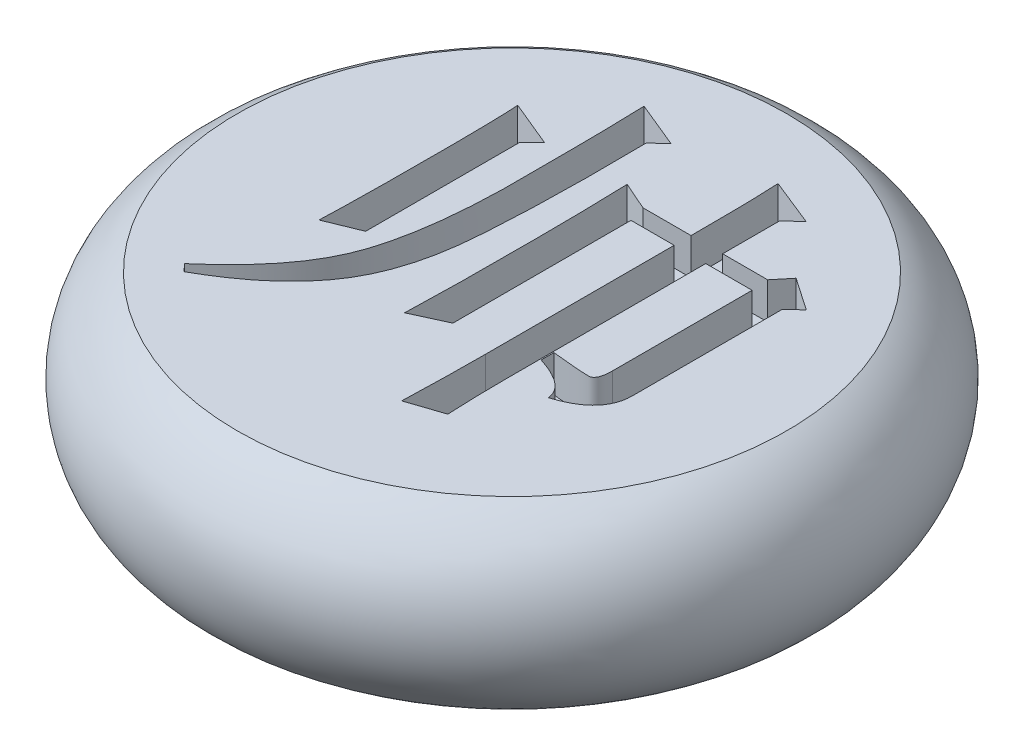
SolidWorks part; units mm, degrees
ref_plane "前视基准面" through (0, 0, 0) normal (0, 0, 1) x (1, 0, 0)
ref_plane "上视基准面" through (0, 0, 0) normal (0, 1, 0) x (1, 0, 0)
ref_plane "右视基准面" through (0, 0, 0) normal (1, 0, 0) x (0, 0, -1)
sketch "草图1" plane through (0, 0, 0) normal (0, 0, 1) x (1, 0, 0)
  line L0 (0, 13.4115) -> (0, -13.4115) construction
  line L1 (0, 0) -> (15, 0)
  line L4 (0, 0) -> (0, 10)
  line L5 (0, 10) -> (15, 10)
  line L6 (-18, 5) -> (18, 5) construction
  arc A1 (15, 0) -> (15, 10) centre (12.3333, 5) ccw
  point P2 (0, 0)
  point P4 (0, 0)
  point P10 (0, 5)
  point P14 (0, 0)
  point P15 (0, 0)
  point P16 (0, 0)
revolve "旋转1" add sketch "草图1" angle 360 about L0
sketch "草图3" plane through (0, 10, 0) normal (0, 1, 0) x (1, 0, 0)
  text T0 "<b>帅</b>" font "宋体" height 15
extrude "切除-拉伸1" cut sketch "草图3" against normal blind 2
